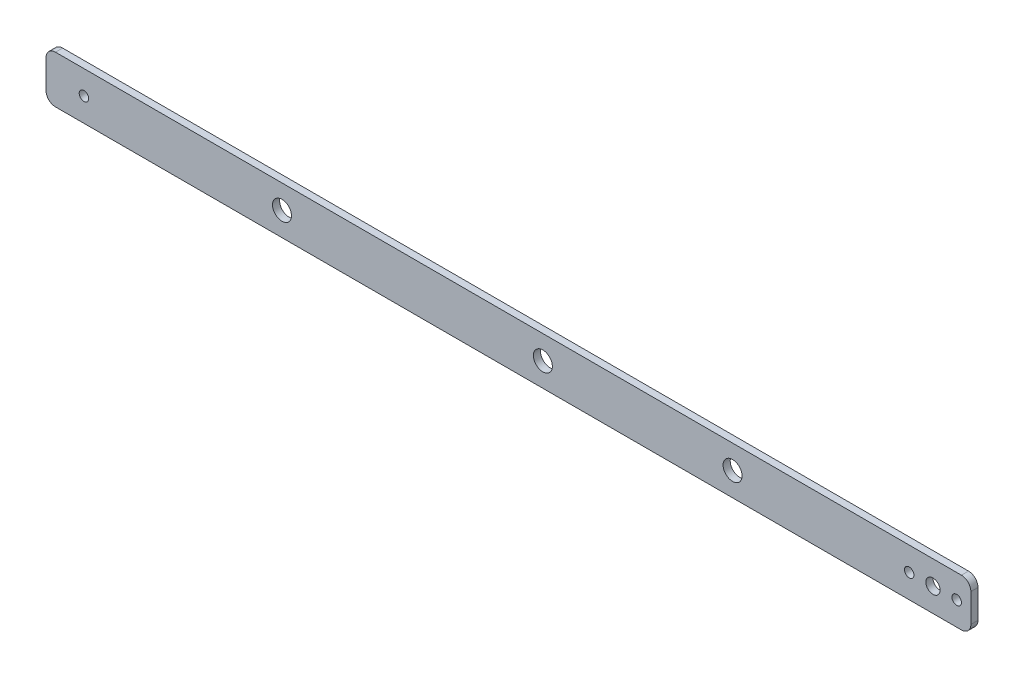
SolidWorks part; units mm, degrees
ref_plane "前视基准面" through (0, 0, 0) normal (0, 0, 1) x (1, 0, 0)
ref_plane "上视基准面" through (0, 0, 0) normal (0, 1, 0) x (1, 0, 0)
ref_plane "右视基准面" through (0, 0, 0) normal (1, 0, 0) x (0, 0, -1)
sketch "草图1" plane through (0, 0, 0) normal (0, 0, 1) x (1, 0, 0)
  line L1 (-200, 0) -> (-5, 0)
  line L2 (-200, 0) -> (-200, -10)
  line L3 (-200, -10) -> (-5, -10)
  line L4 (-5, 0) -> (-5, -10)
  circle A0 centre (-55.2425, -5) radius 2
  circle A1 centre (-95.2425, -5) radius 2
  circle A2 centre (-150.2425, -5) radius 2
  dimension "D1" = 195
  dimension "D2" = 10
extrude "凸台-拉伸1" add sketch "草图1" along normal blind 1.5
sketch "草图2" plane through (0, 0, 1.5) normal (0, 0, 1) x (1, 0, 0)
  line L0 (-200, -5) -> (-192, -5)
  line L1 (-200, 0) -> (-200, -10) construction
  circle A0 centre (-192, -5) radius 1
  dimension "D2" = 2
  dimension "D1" = 8
extrude "切除-拉伸1" cut sketch "草图2" against normal blind 15 and the other way blind 12
ref_plane "基准面1" through (-102.5, 0, 0) normal (-1, 0, 0) x (0, 0, 1)
sketch "草图3" plane through (0, 0, 1.5) normal (0, 0, 1) x (1, 0, 0)
  line L0 (-5, -10) -> (-5, 0) construction
  circle A0 centre (-8, -5) radius 1
  circle A1 centre (-13, -5) radius 1.5
  circle A2 centre (-18, -5) radius 1
  dimension "D1" = 2
  dimension "D2" = 3
  dimension "D3" = 2
  dimension "D4" = 3
  dimension "D5" = 5
  dimension "D6" = 5
extrude "切除-拉伸2" cut sketch "草图3" against normal blind 10 contours A0 | A1 | A2
fillet "圆角1" radius 2 4 edges at (-5, 0, 0.75) (-5, -10, 0.75) (-200, -10, 0.75) (-200, 0, 0.75)
sketch "草图4" plane through (0, 0, 0) normal (0, 0, -1) x (-1, 0, 0)
  line L0 (200, -10) -> (10, -10) construction
  line L1 (128.2354, -10) -> (142.2354, -10)
  line L2 (128.2354, -10) -> (128.2354, -7)
  line L3 (128.2354, -7) -> (142.2354, -7)
  line L4 (142.2354, -10) -> (142.2354, -7)
  line L5 (128.2354, -10) -> (142.2354, -7) construction
  line L6 (128.2354, -7) -> (142.2354, -10) construction
  point P4 (135.2354, -8.5)
  dimension "D1" = 14
  dimension "D2" = 3
